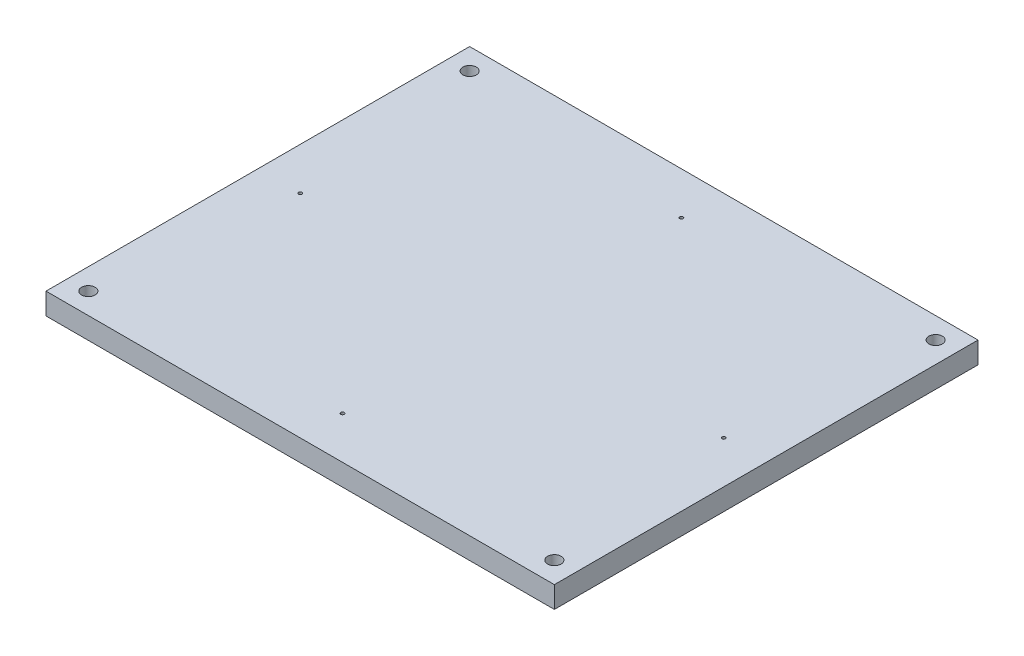
SolidWorks part; units mm, degrees
ref_plane "Plano frontal" through (0, 0, 0) normal (0, 0, 1) x (1, 0, 0)
ref_plane "Plano superior" through (0, 0, 0) normal (0, 1, 0) x (1, 0, 0)
ref_plane "Plano direito" through (0, 0, 0) normal (1, 0, 0) x (0, 0, -1)
sketch "Esboço2" plane through (0, 0, 0) normal (0, 1, 0) x (1, 0, 0)
  line L1 (-600, -500) -> (600, -500)
  line L2 (-600, -500) -> (-600, 500)
  line L3 (-600, 500) -> (600, 500)
  line L4 (600, -500) -> (600, 500)
  line L5 (-600, -500) -> (600, 500) construction
  line L6 (-600, 500) -> (600, -500) construction
  point P0 (0, 0)
  dimension "D1" = 1000
  dimension "D2" = 1200
extrude "Ressalto-extrusão1" add sketch "Esboço2" along normal blind 50.8
sketch "Esboço3" plane through (0, 50.8, 0) normal (0, 1, 0) x (1, 0, 0)
  line L1 (-550, -450) -> (550, -450)
  line L2 (-550, -450) -> (-550, 450)
  line L3 (-550, 450) -> (550, 450)
  line L4 (550, -450) -> (550, 450)
  line L5 (-550, -450) -> (550, 450) construction
  line L6 (-550, 450) -> (550, -450) construction
  circle A0 centre (-550, 450) radius 16
  circle A1 centre (550, 450) radius 16
  circle A2 centre (-550, -450) radius 16
  circle A3 centre (550, -450) radius 16
  point P0 (0, 0)
  dimension "D3" = 32
  dimension "D1" = 900
  dimension "D2" = 1100
extrude "Corte-extrusão1" cut sketch "Esboço3" against normal through all contours L3 A0 L2 | L2 A0 L3 | L4 A1 L3 | L3 A1 L4 | L1 A3 L4 | L4 A3 L1 | L1 A2 L2 | L2 A2 L1
sketch "Esboço4" plane through (0, 50.8, 0) normal (0, 1, 0) x (1, 0, 0)
  line L0 (-500, 0) -> (0, 0)
  line L1 (0, 0) -> (500, 0)
  line L2 (0, 0) -> (0, 400)
  line L3 (0, 0) -> (0, -400)
  dimension "D1" = 500
  dimension "D2" = 500
  dimension "D3" = 400
  dimension "D4" = 400
hole_wizard "Furo de diâmetro Ø8.0 (8)1" positions "Esboço6" profile "Esboço5" hole size "Ø8.0" standard "Ansi Metric"
sketch "Esboço6" plane through (0, 50.8, 0) normal (0, 1, 0) x (1, 0, 0)
  point P0 (-500, 0)
  point P3 (0, 400)
  point P6 (500, 0)
  point P9 (0, -400)
sketch "Esboço5" plane through (-500, 50.8, 0) normal (1, 0, 0) x (0, 0, 1)
  line L0 (0, 0) -> (0, 17.4034)
  line L1 (0, 17.4034) -> (4, 15)
  line L2 (4, 15) -> (4, 0)
  line L5 (4, 0) -> (0, 0)
  line L10 (0, 17.4034) -> (-4, 15) construction
  line L11 (0, -6.35) -> (0, 107.95) construction
  dimension "Hole Dia." = 8
  dimension "Hole Depth" = 15
  dimension "Drill Angle" = 118
